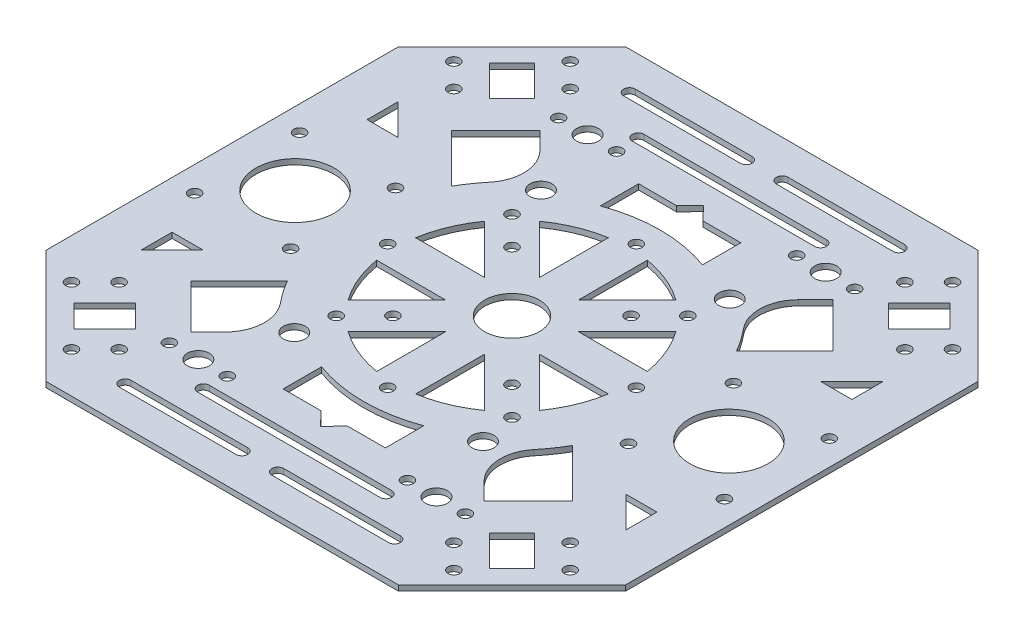
SolidWorks part; units mm, degrees
material "Thornel Mat VMA"
ref_plane "Front Plane" through (0, 0, 0) normal (0, 0, 1) x (1, 0, 0)
ref_plane "Top Plane" through (0, 0, 0) normal (0, 1, 0) x (1, 0, 0)
ref_plane "Right Plane" through (0, 0, 0) normal (1, 0, 0) x (0, 0, -1)
sketch "Sketch1" plane through (0, 0, 0) normal (0, 1, 0) x (1, 0, 0)
  line L0 (-74, 45) -> (-45, 74)
  line L1 (-45, 74) -> (45, 74)
  line L2 (-74, 45) -> (-74, -45)
  line L3 (-45, -74) -> (45, -74)
  line L4 (74, 45) -> (74, -45)
  line L5 (45, 74) -> (74, 45)
  line L6 (74, -45) -> (45, -74)
  line L7 (-45, -74) -> (-74, -45)
  line L8 (0, -51.6391) -> (0, 51.6391) construction
  line L9 (-43.1025, 0) -> (43.1025, 0) construction
  point P0 (0, -74)
  point P11 (0, 74)
  point P12 (-74, 0)
  point P15 (74, 0)
  dimension "D1" = 148
  dimension "D2" = 90
  dimension "D3" = 45
extrude "Boss-Extrude1" add sketch "Sketch1" along normal mid plane 1.4
sketch "Sketch3" plane through (0, 0.7, 0) normal (0, 1, 0) x (1, 0, 0)
  line L0 (-50.9087, 45.1811) -> (-58.7575, 53.03)
  line L1 (-50.9087, 45.1811) -> (-45.1811, 50.9087)
  line L2 (-58.7575, 53.03) -> (-53.03, 58.7575)
  line L3 (-45.1811, 50.9087) -> (-53.03, 58.7575)
  line L8 (0, 0) -> (-48.0449, 48.0449) construction
  line L9 (-63.6719, 48.8227) -> (-57.5908, 42.7416) construction
  line L10 (-45, 74) -> (-74, 45) construction
  line L11 (-48.8227, 63.6719) -> (-42.7416, 57.5908) construction
  line L12 (-63.6719, 48.8227) -> (-48.8227, 63.6719) construction
  line L13 (45.1811, 50.9087) -> (53.03, 58.7575)
  line L14 (45.1811, 50.9087) -> (50.9087, 45.1811)
  line L15 (53.03, 58.7575) -> (58.7575, 53.03)
  line L16 (50.9087, 45.1811) -> (58.7575, 53.03)
  line L21 (48.8227, 63.6719) -> (42.7416, 57.5908) construction
  line L22 (63.6719, 48.8227) -> (57.5908, 42.7416) construction
  line L23 (48.8227, 63.6719) -> (63.6719, 48.8227) construction
  line L24 (50.9087, -45.1811) -> (58.7575, -53.03)
  line L25 (50.9087, -45.1811) -> (45.1811, -50.9087)
  line L26 (58.7575, -53.03) -> (53.03, -58.7575)
  line L27 (45.1811, -50.9087) -> (53.03, -58.7575)
  line L32 (63.6719, -48.8227) -> (57.5908, -42.7416) construction
  line L33 (48.8227, -63.6719) -> (42.7416, -57.5908) construction
  line L34 (63.6719, -48.8227) -> (48.8227, -63.6719) construction
  line L35 (-45.1811, -50.9087) -> (-53.03, -58.7575)
  line L36 (-45.1811, -50.9087) -> (-50.9087, -45.1811)
  line L37 (-53.03, -58.7575) -> (-58.7575, -53.03)
  line L38 (-50.9087, -45.1811) -> (-58.7575, -53.03)
  line L43 (-48.8227, -63.6719) -> (-42.7416, -57.5908) construction
  line L44 (-63.6719, -48.8227) -> (-57.5908, -42.7416) construction
  line L45 (-48.8227, -63.6719) -> (-63.6719, -48.8227) construction
  line L46 (0, -0.77) -> (0, 0.77) construction
  line L47 (-0.77, 0) -> (0.77, 0) construction
  circle A0 centre (-48.8227, 63.6719) radius 1.5
  circle A1 centre (-63.6719, 48.8227) radius 1.5
  circle A2 centre (-57.5908, 42.7416) radius 1.5
  circle A3 centre (-42.7416, 57.5908) radius 1.5
  circle A4 centre (63.6719, 48.8227) radius 1.5
  circle A5 centre (48.8227, 63.6719) radius 1.5
  circle A6 centre (42.7416, 57.5908) radius 1.5
  circle A7 centre (57.5908, 42.7416) radius 1.5
  circle A8 centre (48.8227, -63.6719) radius 1.5
  circle A9 centre (63.6719, -48.8227) radius 1.5
  circle A10 centre (57.5908, -42.7416) radius 1.5
  circle A11 centre (42.7416, -57.5908) radius 1.5
  circle A12 centre (-63.6719, -48.8227) radius 1.5
  circle A13 centre (-48.8227, -63.6719) radius 1.5
  circle A14 centre (-42.7416, -57.5908) radius 1.5
  circle A15 centre (-57.5908, -42.7416) radius 1.5
  point P20 (-48.0449, 48.0449)
  point P21 (-55.8938, 55.8938)
  point P27 (-59.5, 59.5)
  point P77 (0, 0)
  dimension "D7" = 3
  dimension "D2" = 5.1
  dimension "D3" = 11.1
  dimension "D6" = 8.1
  dimension "D8" = 21
  dimension "D9" = 10.5
  dimension "D10" = 4.6
  dimension "D11" = 8.6
  dimension "D12" = 4
extrude "Cut-Extrude1" cut sketch "Sketch3" against normal through all
sketch "Sketch9" plane through (0, 0.7, 0) normal (0, 1, 0) x (1, 0, 0)
  line L0 (-34.4, 64.4) -> (-4.6, 64.4) construction
  line L1 (-34.4, 65.9) -> (-4.6, 65.9)
  line L2 (-34.4, 62.9) -> (-4.6, 62.9)
  line L3 (4.6, 64.4) -> (34.4, 64.4) construction
  line L4 (4.6, 65.9) -> (34.4, 65.9)
  line L5 (4.6, 62.9) -> (34.4, 62.9)
  line L6 (-23.3, 55.5) -> (23.3, 55.5) construction
  line L7 (-23.3, 57) -> (23.3, 57)
  line L8 (-23.3, 54) -> (23.3, 54)
  line L9 (0, -0.77) -> (0, 0.77) construction
  line L10 (45, 74) -> (-45, 74) construction
  line L11 (-4.6, 64.4) -> (4.6, 64.4) construction
  line L12 (-23, 49.7) -> (23, 49.7) construction
  line L13 (-24.1, 31.5) -> (24.1, 31.5) construction
  line L14 (-3.4, 45.3824) -> (0, 48.8824)
  line L15 (-13.05, 45.3824) -> (-3.4, 45.3824)
  line L16 (-13.05, 45.3824) -> (-13.05, 35.5824)
  line L18 (13.05, 45.3824) -> (13.05, 35.5824)
  line L19 (0, 48.8824) -> (3.4, 45.3824)
  line L20 (3.4, 45.3824) -> (13.05, 45.3824)
  line L21 (-0.77, 0) -> (0.77, 0) construction
  line L22 (-34.4, -64.4) -> (-4.6, -64.4) construction
  line L23 (-34.4, -65.9) -> (-4.6, -65.9)
  line L24 (-34.4, -62.9) -> (-4.6, -62.9)
  line L25 (4.6, -64.4) -> (34.4, -64.4) construction
  line L26 (4.6, -65.9) -> (34.4, -65.9)
  line L27 (4.6, -62.9) -> (34.4, -62.9)
  line L28 (-23.3, -55.5) -> (23.3, -55.5) construction
  line L29 (-23.3, -57) -> (23.3, -57)
  line L30 (-23.3, -54) -> (23.3, -54)
  line L31 (-24.1, -31.5) -> (24.1, -31.5) construction
  line L32 (-23, -49.7) -> (23, -49.7) construction
  line L33 (-4.6, -64.4) -> (4.6, -64.4) construction
  line L34 (3.4, -45.3824) -> (13.05, -45.3824)
  line L35 (0, -48.8824) -> (3.4, -45.3824)
  line L36 (13.05, -45.3824) -> (13.05, -35.5824)
  line L37 (-13.05, -45.3824) -> (-13.05, -35.5824)
  line L38 (-13.05, -45.3824) -> (-3.4, -45.3824)
  line L39 (-3.4, -45.3824) -> (0, -48.8824)
  arc A0 (-34.4, 65.9) -> (-34.4, 62.9) centre (-34.4, 64.4) ccw
  arc A1 (-4.6, 62.9) -> (-4.6, 65.9) centre (-4.6, 64.4) ccw
  arc A2 (4.6, 65.9) -> (4.6, 62.9) centre (4.6, 64.4) ccw
  arc A3 (34.4, 62.9) -> (34.4, 65.9) centre (34.4, 64.4) ccw
  arc A4 (-23.3, 57) -> (-23.3, 54) centre (-23.3, 55.5) ccw
  arc A5 (23.3, 54) -> (23.3, 57) centre (23.3, 55.5) ccw
  circle A6 centre (-37.8, 49.7) radius 1.5
  circle A7 centre (-30.4, 49.7) radius 2.8
  circle A8 centre (-23, 49.7) radius 1.5
  circle A9 centre (23, 49.7) radius 1.5
  circle A10 centre (30.4, 49.7) radius 2.8
  circle A11 centre (37.8, 49.7) radius 1.5
  circle A12 centre (-24.1, 31.5) radius 2.8
  circle A13 centre (24.1, 31.5) radius 2.8
  arc A14 (13.05, 35.5824) -> (-13.05, 35.5824) centre (0, 0) ccw
  arc A15 (-34.4, -65.9) -> (-34.4, -62.9) centre (-34.4, -64.4) cw
  arc A16 (-4.6, -62.9) -> (-4.6, -65.9) centre (-4.6, -64.4) cw
  arc A17 (4.6, -65.9) -> (4.6, -62.9) centre (4.6, -64.4) cw
  arc A18 (34.4, -62.9) -> (34.4, -65.9) centre (34.4, -64.4) cw
  arc A19 (-23.3, -57) -> (-23.3, -54) centre (-23.3, -55.5) cw
  arc A20 (23.3, -54) -> (23.3, -57) centre (23.3, -55.5) cw
  arc A21 (13.05, -35.5824) -> (-13.05, -35.5824) centre (0, 0) cw
  circle A22 centre (24.1, -31.5) radius 2.8
  circle A23 centre (-24.1, -31.5) radius 2.8
  circle A24 centre (37.8, -49.7) radius 1.5
  circle A25 centre (30.4, -49.7) radius 2.8
  circle A26 centre (23, -49.7) radius 1.5
  circle A27 centre (-23, -49.7) radius 1.5
  circle A28 centre (-30.4, -49.7) radius 2.8
  circle A29 centre (-37.8, -49.7) radius 1.5
  point P2 (-19.5, 64.4)
  point P7 (19.5, 64.4)
  point P14 (0, 55.5)
  point P37 (0, 64.4)
  point P40 (0, 49.7)
  point P41 (0, 31.5)
  point P61 (-19.5, -64.4)
  point P68 (19.5, -64.4)
  point P75 (0, -55.5)
  dimension "D2" = 1.5
  dimension "D9" = 5.6
  dimension "D16" = 37.9
  dimension "D1" = 8.1
  dimension "D3" = 9.2
  dimension "D4" = 29.8
  dimension "D5" = 46.6
  dimension "D6" = 17
  dimension "D7" = 46
  dimension "D8" = 24.3
  dimension "D10" = 7.4
  dimension "D11" = 7.4
  dimension "D12" = 7.4
  dimension "D13" = 7.4
  dimension "D14" = 48.2
  dimension "D15" = 42.5
  dimension "D17" = 26.1
  dimension "D18" = 9.8
  dimension "D19" = 3.5
  dimension "D20" = 6.8
extrude "Cut-Extrude5" cut sketch "Sketch9" against normal through all
sketch "Sketch10" plane through (0, 0.7, 0) normal (0, 1, 0) x (1, 0, 0)
  line L0 (-0.77, 0) -> (0.77, 0) construction
  line L1 (-74, 45) -> (-74, -45) construction
  line L2 (-67.65, 13.4) -> (-43.15, 13.4) construction
  line L3 (-67.65, 13.4) -> (-67.65, -13.4) construction
  line L4 (-67.65, -13.4) -> (-43.15, -13.4) construction
  line L5 (-43.15, 13.4) -> (-43.15, -13.4) construction
  line L6 (-61.9, 32.8) -> (-61.9, 24.9)
  line L7 (-61.9, 24.9) -> (-54, 24.9)
  line L8 (-54, 24.9) -> (-61.9, 32.8)
  line L9 (-61.9, -24.9) -> (-61.9, -32.8)
  line L10 (-61.9, -32.8) -> (-54, -24.9)
  line L11 (-54, -24.9) -> (-61.9, -24.9)
  line L12 (-54, 24.9) -> (-54, -24.9) construction
  line L13 (-48.7166, 33.231) -> (-36.4142, 20.9286)
  line L14 (-48.7166, 33.231) -> (-37.4029, 44.5447)
  line L16 (-37.4029, 44.5447) -> (-33.0317, 40.1735)
  line L17 (-50.9087, 45.1811) -> (-45.1811, 50.9087) construction
  line L18 (-58.7575, 53.03) -> (-50.9087, 45.1811) construction
  line L19 (-37.4029, -44.5447) -> (-33.0317, -40.1735)
  line L20 (-48.7166, -33.231) -> (-37.4029, -44.5447)
  line L21 (-48.7166, -33.231) -> (-36.4142, -20.9286)
  line L22 (0, -0.77) -> (0, 0.77) construction
  line L23 (54, 24.9) -> (54, -24.9) construction
  line L24 (43.15, 13.4) -> (43.15, -13.4) construction
  line L25 (67.65, -13.4) -> (43.15, -13.4) construction
  line L26 (67.65, 13.4) -> (67.65, -13.4) construction
  line L27 (67.65, 13.4) -> (43.15, 13.4) construction
  line L28 (48.7166, -33.231) -> (36.4142, -20.9286)
  line L29 (48.7166, -33.231) -> (37.4029, -44.5447)
  line L30 (37.4029, -44.5447) -> (33.0317, -40.1735)
  line L31 (37.4029, 44.5447) -> (33.0317, 40.1735)
  line L32 (48.7166, 33.231) -> (37.4029, 44.5447)
  line L33 (48.7166, 33.231) -> (36.4142, 20.9286)
  line L34 (54, -24.9) -> (61.9, -24.9)
  line L35 (61.9, -32.8) -> (54, -24.9)
  line L36 (61.9, -24.9) -> (61.9, -32.8)
  line L37 (54, 24.9) -> (61.9, 32.8)
  line L38 (61.9, 24.9) -> (54, 24.9)
  line L39 (61.9, 32.8) -> (61.9, 24.9)
  circle A0 centre (-55.4, 0) radius 10
  circle A1 centre (-67.65, 13.4) radius 1.5
  circle A2 centre (-43.15, 13.4) radius 1.5
  circle A3 centre (-43.15, -13.4) radius 1.5
  circle A4 centre (-67.65, -13.4) radius 1.5
  arc A5 (-32.3907, 26.7366) -> (-36.4142, 20.9286) centre (0, 0) ccw
  arc A6 (-32.3907, 26.7366) -> (-33.0317, 40.1735) centre (-40.1028, 33.1024) ccw
  arc A7 (-32.3907, -26.7366) -> (-33.0317, -40.1735) centre (-40.1028, -33.1024) cw
  arc A8 (-32.3907, -26.7366) -> (-36.4142, -20.9286) centre (0, 0) cw
  arc A9 (32.3907, -26.7366) -> (36.4142, -20.9286) centre (0, 0) ccw
  arc A10 (32.3907, -26.7366) -> (33.0317, -40.1735) centre (40.1028, -33.1024) ccw
  arc A11 (32.3907, 26.7366) -> (33.0317, 40.1735) centre (40.1028, 33.1024) cw
  arc A12 (32.3907, 26.7366) -> (36.4142, 20.9286) centre (0, 0) cw
  circle A13 centre (67.65, -13.4) radius 1.5
  circle A14 centre (43.15, -13.4) radius 1.5
  circle A15 centre (43.15, 13.4) radius 1.5
  circle A16 centre (67.65, 13.4) radius 1.5
  circle A17 centre (55.4, 0) radius 10
  point P13 (-43.15, 0)
  point P16 (-55.4, 13.4)
  point P21 (-54, 0)
  dimension "D1" = 20
  dimension "D3" = 26.8
  dimension "D5" = 3
  dimension "D12" = 84
  dimension "D13" = 10
  dimension "D2" = 24.5
  dimension "D4" = 18.6
  dimension "D6" = 7.9
  dimension "D7" = 12.1
  dimension "D8" = 49.8
  dimension "D9" = 16
  dimension "D10" = 9.1
  dimension "D11" = 10
extrude "Cut-Extrude6" cut sketch "Sketch10" against normal through all
sketch "Sketch11" plane through (0, 0.7, 0) normal (0, 1, 0) x (1, 0, 0)
  line L3 (-17.4017, 24.4373) -> (-4.9749, 12.0104)
  line L4 (-4.9749, 12.0104) -> (-4.9749, 29.5846)
  line L5 (-11.4805, 27.7164) -> (0, 0) construction
  line L6 (0, -0.77) -> (0, 0.77) construction
  line L7 (4.9749, 29.5846) -> (4.9749, 12.0104)
  line L8 (4.9749, 12.0104) -> (17.4017, 24.4373)
  line L9 (11.4805, 27.7164) -> (0, 0) construction
  line L10 (24.4373, 17.4017) -> (12.0104, 4.9749)
  line L11 (12.0104, 4.9749) -> (29.5846, 4.9749)
  line L12 (27.7164, 11.4805) -> (0, 0) construction
  line L13 (29.5846, -4.9749) -> (12.0104, -4.9749)
  line L14 (12.0104, -4.9749) -> (24.4373, -17.4017)
  line L15 (27.7164, -11.4805) -> (0, 0) construction
  line L16 (17.4017, -24.4373) -> (4.9749, -12.0104)
  line L17 (4.9749, -12.0104) -> (4.9749, -29.5846)
  line L18 (11.4805, -27.7164) -> (0, 0) construction
  line L19 (-4.9749, -29.5846) -> (-4.9749, -12.0104)
  line L20 (-4.9749, -12.0104) -> (-17.4017, -24.4373)
  line L21 (-11.4805, -27.7164) -> (0, 0) construction
  line L22 (-24.4373, -17.4017) -> (-12.0104, -4.9749)
  line L23 (-12.0104, -4.9749) -> (-29.5846, -4.9749)
  line L24 (-27.7164, -11.4805) -> (0, 0) construction
  line L25 (-29.5846, 4.9749) -> (-12.0104, 4.9749)
  line L26 (-12.0104, 4.9749) -> (-24.4373, 17.4017)
  line L27 (-27.7164, 11.4805) -> (0, 0) construction
  line L29 (0, 0) -> (15.2028, 15.2028) construction
  line L30 (-0.77, 0) -> (0.77, 0) construction
  circle A0 centre (0, 0) radius 7
  arc A2 (-4.9749, 29.5846) -> (-17.4017, 24.4373) centre (0, 0) ccw
  arc A3 (17.4017, 24.4373) -> (4.9749, 29.5846) centre (0, 0) ccw
  arc A4 (29.5846, 4.9749) -> (24.4373, 17.4017) centre (0, 0) ccw
  arc A5 (24.4373, -17.4017) -> (29.5846, -4.9749) centre (0, 0) ccw
  arc A6 (4.9749, -29.5846) -> (17.4017, -24.4373) centre (0, 0) ccw
  arc A7 (-17.4017, -24.4373) -> (-4.9749, -29.5846) centre (0, 0) ccw
  arc A8 (-29.5846, -4.9749) -> (-24.4373, -17.4017) centre (0, 0) ccw
  arc A9 (-24.4373, 17.4017) -> (-29.5846, 4.9749) centre (0, 0) ccw
  circle A10 centre (15.2028, 15.2028) radius 1.5
  circle A12 centre (0, 31.75) radius 1.5
  circle A13 centre (22.4506, 22.4506) radius 1.5
  circle A14 centre (31.75, 0) radius 1.5
  circle A15 centre (22.4506, -22.4506) radius 1.5
  circle A16 centre (0, -31.75) radius 1.5
  circle A17 centre (-22.4506, -22.4506) radius 1.5
  circle A18 centre (-31.75, 0) radius 1.5
  circle A19 centre (-22.4506, 22.4506) radius 1.5
  circle A20 centre (15.2028, -15.2028) radius 1.5
  circle A21 centre (-15.2028, -15.2028) radius 1.5
  circle A22 centre (-15.2028, 15.2028) radius 1.5
  point P39 (0, 0)
  point P60 (0, 0)
  point P68 (0, 0)
  dimension "D1" = 14
  dimension "D2" = 30
  dimension "D8" = 3
  dimension "D3" = 17
  dimension "D4" = 45
  dimension "D6" = 31.75
  dimension "D7" = 45
  dimension "D9" = 21.5
  dimension "D5" = 8
  dimension "D10" = 8
  dimension "D11" = 4
extrude "Cut-Extrude7" cut sketch "Sketch11" against normal through all
